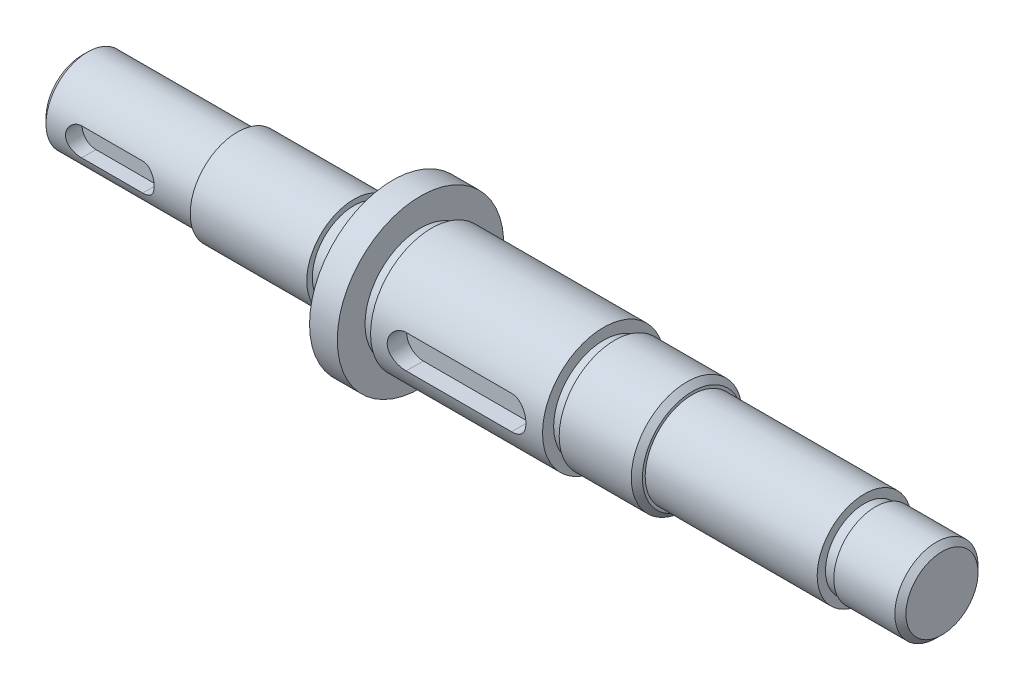
SolidWorks part; units mm, degrees
ref_plane "前视基准面" through (0, 0, 0) normal (0, 0, 1) x (1, 0, 0)
ref_plane "上视基准面" through (0, 0, 0) normal (0, 1, 0) x (1, 0, 0)
ref_plane "右视基准面" through (0, 0, 0) normal (1, 0, 0) x (0, 0, -1)
sketch "草图1" plane through (0, 0, 0) normal (0, 0, 1) x (1, 0, 0)
  line L0 (0, 0) -> (155, 0) construction
  line L1 (0, 0) -> (0, 7.5)
  line L2 (0, 7.5) -> (28, 7.5)
  line L3 (28, 7.5) -> (28, 8.5)
  line L4 (28, 8.5) -> (49, 8.5)
  line L5 (49, 8.5) -> (49, 7.5)
  line L6 (49, 7.5) -> (51, 7.5)
  line L7 (51, 7.5) -> (51, 5)
  line L8 (51, 5) -> (56, 5)
  line L9 (56, 5) -> (56, 15)
  line L10 (56, 15) -> (61, 15)
  line L11 (61, 15) -> (61, 10)
  line L12 (61, 10) -> (63, 10)
  line L13 (63, 10) -> (63, 11)
  line L14 (63, 11) -> (94, 11)
  line L15 (94, 11) -> (94, 9)
  line L16 (94, 9) -> (96, 9)
  line L17 (96, 9) -> (96, 10)
  line L18 (96, 10) -> (110, 10)
  line L19 (110, 10) -> (110, 8.5)
  line L20 (110, 8.5) -> (141, 8.5)
  line L21 (141, 8.5) -> (141, 7)
  line L22 (141, 7) -> (143, 7)
  line L23 (143, 7) -> (143, 7.5)
  line L24 (143, 7.5) -> (155, 7.5)
  line L25 (155, 7.5) -> (155, 0)
  line L26 (0, 0) -> (155, 0)
  dimension "D1" = 7.5
  dimension "D2" = 28
  dimension "D3" = 21
  dimension "D4" = 8.5
  dimension "D5" = 7.5
  dimension "D6" = 2
  dimension "D7" = 5
  dimension "D8" = 5
  dimension "D9" = 5
  dimension "D10" = 15
  dimension "D11" = 10
  dimension "D12" = 2
  dimension "D13" = 31
  dimension "D14" = 11
  dimension "D15" = 9
  dimension "D16" = 2
  dimension "D17" = 14
  dimension "D18" = 10
  dimension "D19" = 31
  dimension "D20" = 8.5
  dimension "D21" = 2
  dimension "D22" = 7
  dimension "D23" = 12
  dimension "D24" = 7.5
revolve "旋转1" add sketch "草图1" angle 360 about L0
ref_plane "基准面1" through (0, 0, 7.5) normal (0, 0, 1) x (1, 0, 0)
sketch "草图2" plane through (0, 0, 7.5) normal (0, 0, 1) x (1, 0, 0)
  line L0 (18, 0) -> (7, 0) construction
  line L1 (18, -2.5) -> (7, -2.5)
  line L2 (18, 2.5) -> (7, 2.5)
  line L3 (0, 7.5) -> (0, -7.5) construction
  arc A0 (18, -2.5) -> (18, 2.5) centre (18, 0) ccw
  arc A1 (7, 2.5) -> (7, -2.5) centre (7, 0) ccw
  point P3 (12.5, 0)
  point P10 (5.0368, 0.8715)
  point P11 (12.5, -2.5)
  dimension "D1" = 11
  dimension "D2" = 7
  dimension "D3" = 5
extrude "切除-拉伸1" cut sketch "草图2" against normal blind 3
ref_plane "基准面2" through (0, 0, 11) normal (0, 0, 1) x (-1, 0, 0)
sketch "草图3" plane through (0, 0, 11) normal (0, 0, 1) x (-1, 0, 0)
  line L0 (-88, 0) -> (-69, 0) construction
  line L1 (-88, 3) -> (-69, 3)
  line L2 (-88, -3) -> (-69, -3)
  line L3 (-63, -11) -> (-63, 11) construction
  arc A0 (-88, 3) -> (-88, -3) centre (-88, 0) ccw
  arc A1 (-69, -3) -> (-69, 3) centre (-69, 0) ccw
  point P3 (-78.5, 0)
  dimension "D1" = 19
  dimension "D2" = 6
  dimension "D3" = 6
extrude "切除-拉伸2" cut sketch "草图3" against normal blind 3.5
chamfer "倒角1" distance 1 angle 45 3 edges at (0, 0, 7.5) (155, 0, 7.5) (110, 0, 10)
